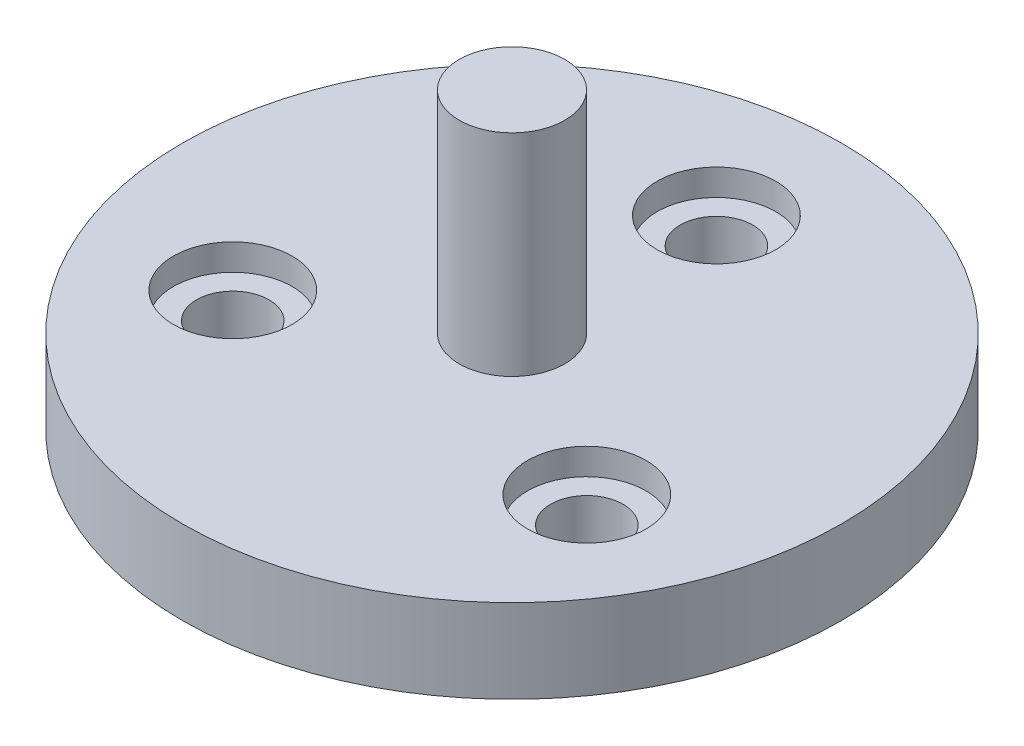
SolidWorks part; units mm, degrees
material "ABS"
ref_plane "Front Plane" through (0, 0, 0) normal (0, 0, 1) x (1, 0, 0)
ref_plane "Top Plane" through (0, 0, 0) normal (0, 1, 0) x (1, 0, 0)
ref_plane "Right Plane" through (0, 0, 0) normal (1, 0, 0) x (0, 0, -1)
sketch "Sketch1" plane through (0, 0, 0) normal (1, 0, 0) x (0, 0, -1)
  line L0 (0, -6.35) -> (0, 16)
  line L1 (0, 16) -> (-4, 16)
  line L2 (-4, 16) -> (-4, 0)
  line L3 (-4, 0) -> (-25, 0)
  line L4 (-25, 0) -> (-25, -6.35)
  line L5 (-25, -6.35) -> (0, -6.35)
  dimension "D1" = 6.35
  dimension "D2" = 25
  dimension "D3" = 4
  dimension "D4" = 16
revolve "Revolve1" add sketch "Sketch1" angle 360 about L0
hole_wizard "CBORE for M5 SHCS1" positions "Sketch2" profile "Sketch3" counterbore size "M5" standard "ANSI Metric" end condition up to next
sketch "Sketch2" plane through (0, 0, 0) normal (0, -1, 0) x (-1, 0, 0)
  line L0 (0, 15.5) -> (0, 0) construction
  line L1 (0, 0) -> (13.4234, -7.75) construction
  line L3 (-13.4234, -7.75) -> (0, 0) construction
  point P1 (0, 15.5)
  point P5 (13.4234, -7.75)
  point P7 (-13.4234, -7.75)
  dimension "D1" = 120
  dimension "D2" = 120
  dimension "D3" = 15.5
sketch "Sketch3" plane through (0, 0, -15.5) normal (1, 0, 0) x (0, 0, 1)
  line L0 (0, 0) -> (0, 6.35)
  line L1 (0, 6.35) -> (2.75, 6.35)
  line L3 (2.75, 6.35) -> (2.75, 2)
  line L4 (2.75, 2) -> (4.5, 2)
  line L5 (4.5, 2) -> (4.5, 0)
  line L7 (4.5, 0) -> (0, 0)
  line L11 (0, -6.35) -> (0, 107.95) construction
  dimension "Thru Hole Dia." = 5.5
  dimension "Thru Hole Depth" = 6.35
  dimension "C'Bore Dia." = 9
  dimension "C'Bore Depth" = 2
